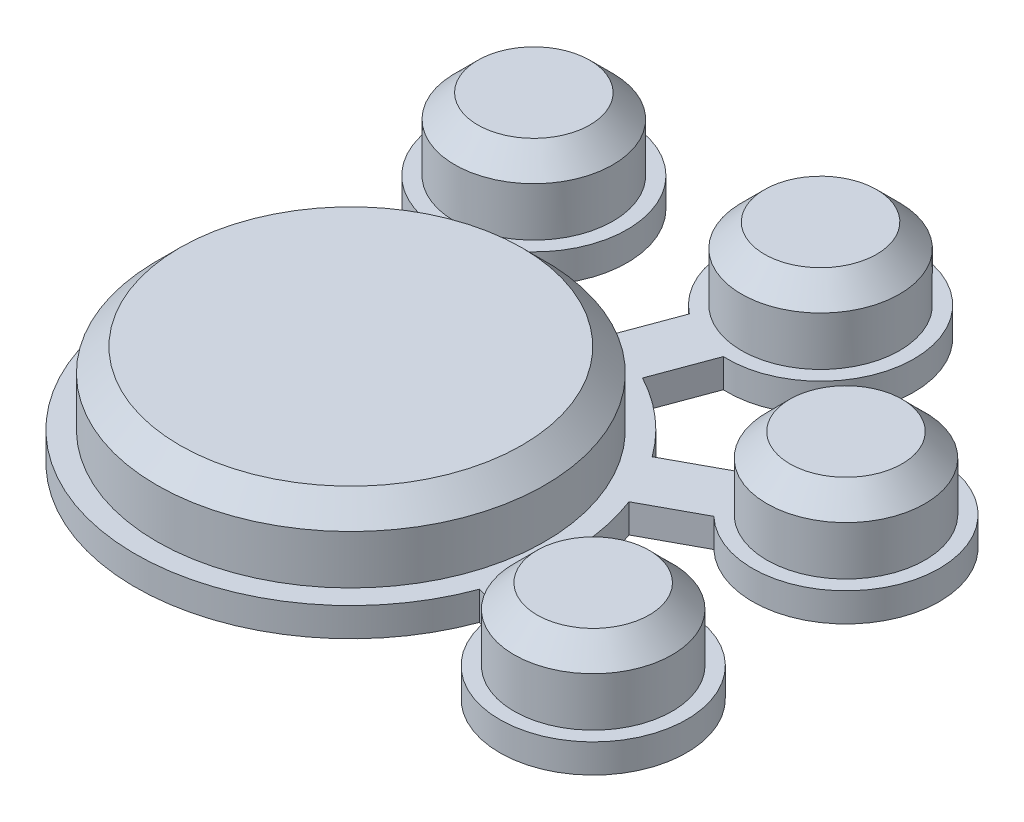
SolidWorks part; units mm, degrees
ref_plane "前视基准面" through (0, 0, 0) normal (0, 0, 1) x (1, 0, 0)
ref_plane "上视基准面" through (0, 0, 0) normal (0, 1, 0) x (1, 0, 0)
ref_plane "右视基准面" through (0, 0, 0) normal (1, 0, 0) x (0, 0, -1)
other "Configuration Table"
sketch "草图1" plane through (0, 0, 0) normal (0, 1, 0) x (1, 0, 0)
  line L0 (1.2, 1.4) -> (1.2, -9.6) construction
  line L1 (1.2, 1.4) -> (11.3256, -2.898) construction
  line L2 (1.2, 1.4) -> (11.1694, 6.0488) construction
  line L3 (1.2, 1.4) -> (4.4161, 11.9194) construction
  line L4 (1.2, 1.4) -> (-4.4654, 10.8288) construction
  line L5 (0, 0) -> (11.3256, -2.898) construction
  line L6 (0, 0) -> (11.1694, 6.0488) construction
  line L7 (0, 0) -> (4.4161, 11.9194) construction
  line L8 (0, 0) -> (-4.4654, 10.8288) construction
  line L9 (8.0761, -2.8407) -> (7.0436, -2.5765)
  line L10 (7.4154, -1.1233) -> (8.4479, -1.3875)
  line L11 (8.9264, 3.6969) -> (7.0123, 2.6603)
  line L12 (7.974, 5.4556) -> (6.0599, 4.419)
  line L13 (4.2795, 8.6722) -> (3.5201, 6.6226)
  line L14 (2.404, 9.3671) -> (1.6447, 7.3174)
  line L15 (-2.5665, 8.1913) -> (-2.1515, 7.1848)
  line L16 (-3.9532, 7.6195) -> (-3.5382, 6.613)
  circle A0 centre (0, 0) radius 7.5
  circle A1 centre (1.2, 1.4) radius 11 construction
  circle A2 centre (-4.4654, 10.8288) radius 3.25
  circle A3 centre (4.4161, 11.9194) radius 3.25
  circle A4 centre (11.1694, 6.0488) radius 3.25
  circle A5 centre (11.3256, -2.898) radius 3.25
  dimension "D1" = 15
  dimension "D2" = 22
  dimension "D9" = 6.5
  dimension "D3" = 1.2
  dimension "D4" = 1.4
  dimension "D5" = 67
  dimension "D6" = 48
  dimension "D7" = 48
  dimension "D8" = 48
  dimension "D10" = 1.5
  dimension "D11" = 2
  dimension "D12" = 2
  dimension "D13" = 1.5
  dimension "D14" = 0.75
  dimension "D15" = 1
  dimension "D16" = 1
  dimension "D17" = 0.75
extrude "凸台-拉伸1" add sketch "草图1" along normal blind 1 contours A2 | A2 L16 A0 L15 | A0 | A3 | A3 L14 A0 L13 | A4 L12 A0 L11 | A4 | A5 | A5 L10 A0 L9
sketch "草图2" plane through (0, 1, 0) normal (0, 1, 0) x (1, 0, 0)
  circle A0 centre (0, 0) radius 6.75
  circle A1 centre (-4.4654, 10.8288) radius 2.75
  circle A2 centre (4.4161, 11.9194) radius 2.75
  circle A3 centre (11.1694, 6.0488) radius 2.75
  circle A4 centre (11.3256, -2.898) radius 2.75
  dimension "D1" = 13.5
  dimension "D2" = 5.5
extrude "凸台-拉伸2" add sketch "草图2" along normal blind 2.5
chamfer "倒角1" distance 0.8 angle 45 5 edges at (0, 3.5, 6.75) (11.3256, 3.5, 5.648) (11.1694, 3.5, -3.2988) (4.4161, 3.5, -9.1694) (-4.4654, 3.5, -8.0788)
sketch "草图3" plane through (0, 0, 0) normal (0, -1, 0) x (1, 0, 0)
  circle A0 centre (0, 0) radius 1
  circle A1 centre (11.3256, 2.898) radius 1
  circle A2 centre (11.1694, -6.0488) radius 1
  circle A3 centre (4.4161, -11.9194) radius 1
  circle A4 centre (-4.4654, -10.8288) radius 1
  dimension "D1" = 2
extrude "凸台-拉伸3" add sketch "草图3" along normal blind 0.55
